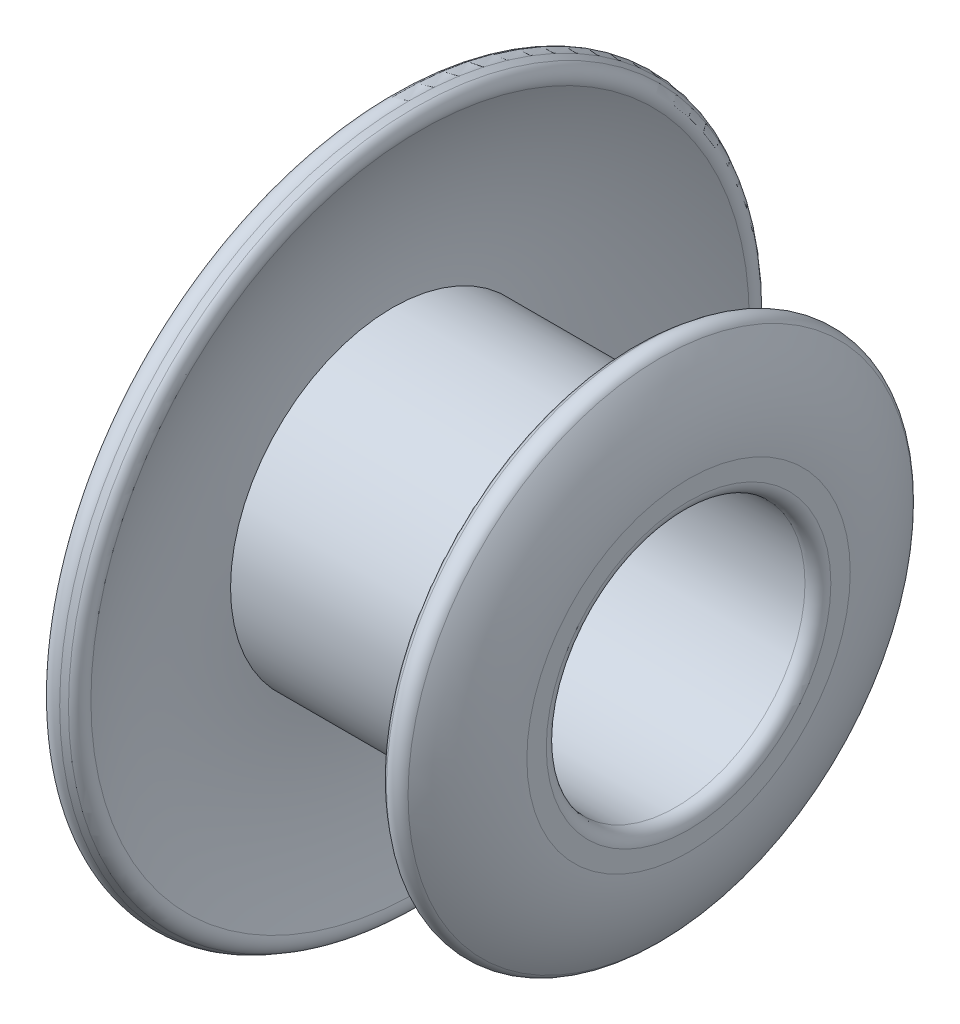
SolidWorks part; units mm, degrees
ref_plane "Front Plane" through (0, 0, 0) normal (0, 0, 1) x (1, 0, 0)
ref_plane "Top Plane" through (0, 0, 0) normal (0, 1, 0) x (1, 0, 0)
ref_plane "Right Plane" through (0, 0, 0) normal (1, 0, 0) x (0, 0, -1)
sketch "Sketch1" plane through (0, 0, 0) normal (0, 0, 1) x (1, 0, 0)
  line L0 (0, 0) -> (-2.5569, 0) construction
  line L1 (0, 1.25) -> (-2, 1.25)
  line L2 (-2.25, 1) -> (0.25, 1)
  line L3 (-2, 1.25) -> (-2.0406, 1.25)
  line L4 (-2, 2.75) -> (-1.781, 2.6294)
  line L5 (0.25, 1) -> (0.25, 1.25)
  line L6 (-0.031, 2.0396) -> (-0.2248, 1.8817)
  arc A0 (-2.25, 1) -> (-2, 2.75) centre (0.19, 1.5443) cw
  arc A1 (-2.0406, 1.25) -> (-1.781, 2.6294) centre (0.19, 1.5443) cw
  arc A2 (-2.006, 1.0544) -> (-1.781, 2.6294) centre (0.19, 1.5443) cw construction
  arc A3 (0.25, 1.25) -> (-0.031, 2.0396) centre (-1, 1.25) ccw
  arc A4 (0, 1.25) -> (-0.2248, 1.8817) centre (-1, 1.25) ccw
  dimension "D6" = 2.5
  dimension "D9" = 1.25
  dimension "D1" = 1.25
  dimension "D2" = 2
  dimension "D3" = 0.25
  dimension "D4" = 0.25
  dimension "D5" = 0.25
  dimension "D7" = 1.5
  dimension "D10" = 1.75
  dimension "D8" = 0.25
  dimension "D11" = 0.25
revolve "Revolve1" add sketch "Sketch1" angle 360 about L0
fillet "Fillet1" radius 0.1 6 edges at (-2.25, 0, -1) (0.25, 0, -1) (-0.2248, 0, -1.8817) (-1.781, 0, -2.6294) (-0.031, 0, -2.0396) (-2, 0, -2.75)
